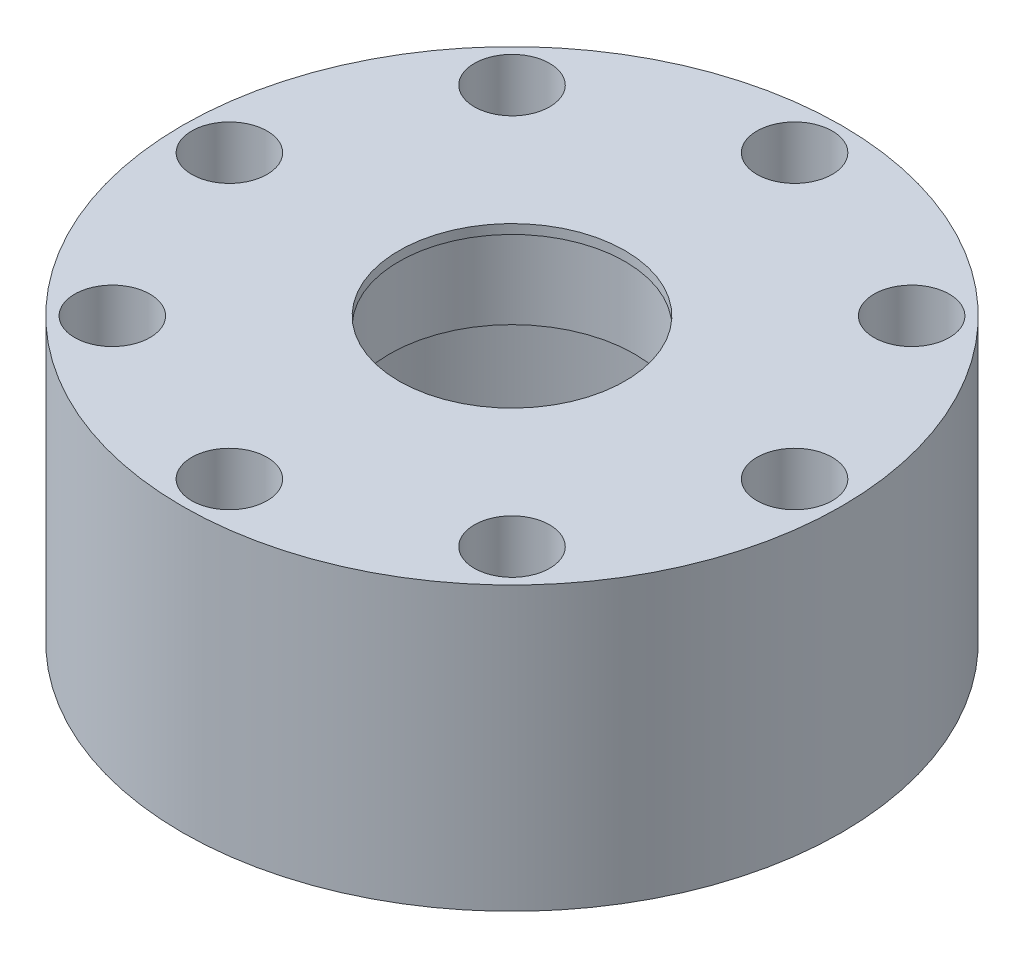
SolidWorks part; units mm, degrees
ref_plane "Front Plane" through (0, 0, 0) normal (0, 0, 1) x (1, 0, 0)
ref_plane "Top Plane" through (0, 0, 0) normal (0, 1, 0) x (1, 0, 0)
ref_plane "Right Plane" through (0, 0, 0) normal (1, 0, 0) x (0, 0, -1)
sketch "Sketch1" plane through (0, 0, 0) normal (0, 0, 1) x (1, 0, 0)
  line L0 (12.5, 0) -> (17.5, 0)
  line L1 (17.5, 0) -> (17.5, 15)
  line L4 (6.5, 10) -> (7.5, 10)
  line L5 (12.5, 10) -> (12.5, 0)
  line L6 (0, 0) -> (0, 14.6637) construction
  line L7 (10, 10) -> (10, 12)
  line L8 (10, 12) -> (7.5, 12)
  line L9 (7.5, 12) -> (7.5, 10)
  line L10 (10, 10) -> (12.5, 10)
  line L13 (6, 15) -> (17.5, 15)
  line L14 (6.5, 10) -> (6.5, 14.5)
  line L15 (6.5, 14.5) -> (6, 14.5)
  line L16 (6, 14.5) -> (6, 15)
  point P12 (6.5675, 10)
  dimension "D1" = 35
  dimension "D2" = 25
  dimension "D3" = 0.5
  dimension "D4" = 10
  dimension "D5" = 20
  dimension "D6" = 15
  dimension "D7" = 2
  dimension "D8" = 5
  dimension "D9" = 0.5
  dimension "D10" = 1
revolve "Revolve1" add sketch "Sketch1" angle 360 about L6
sketch "Sketch2" plane through (0, 15, 0) normal (0, 1, 0) x (1, 0, 0)
  line L0 (0, 0) -> (15, 0) construction
  line L1 (0, 0) -> (10.6066, -10.6066) construction
  circle A0 centre (15, 0) radius 2
  circle A1 centre (0, 0) radius 15 construction
  circle A2 centre (10.6066, -10.6066) radius 2
  circle A3 centre (0, -15) radius 2
  circle A4 centre (-10.6066, -10.6066) radius 2
  circle A5 centre (-15, 0) radius 2
  circle A6 centre (-10.6066, 10.6066) radius 2
  circle A7 centre (0, 15) radius 2
  circle A8 centre (10.6066, 10.6066) radius 2
  point P2 (10.6066, -10.6066)
  point P6 (0, 0)
  dimension "D1" = 4
  dimension "D2" = 30
  dimension "D4" = 45
  dimension "D3" = 8
extrude "Cut-Extrude1" cut sketch "Sketch2" against normal through all
